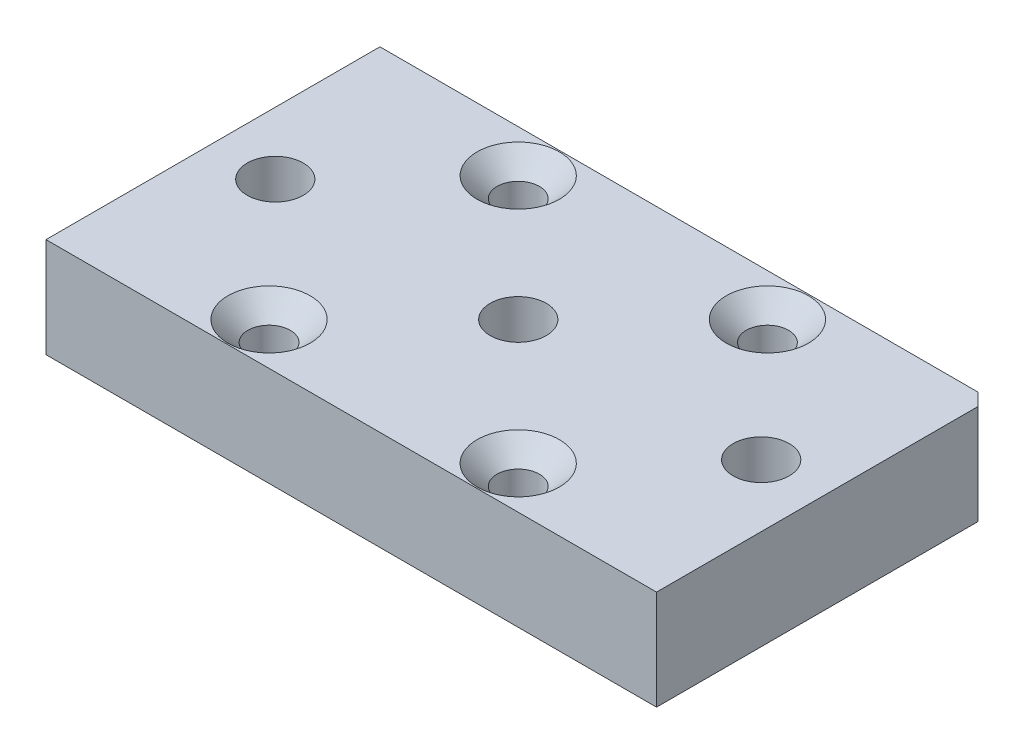
SolidWorks part; units mm, degrees
ref_plane "前视基准面" through (0, 0, 0) normal (0, 0, 1) x (1, 0, 0)
ref_plane "上视基准面" through (0, 0, 0) normal (0, 1, 0) x (1, 0, 0)
ref_plane "右视基准面" through (0, 0, 0) normal (1, 0, 0) x (0, 0, -1)
other "Configuration Table"
sketch "草图1" plane through (0, 0, 0) normal (0, 1, 0) x (1, 0, 0)
  line L1 (-24.5, -13.4) -> (24.5, -13.4)
  line L2 (-24.5, -13.4) -> (-24.5, 13.4)
  line L3 (-24.5, 13.4) -> (24.5, 13.4)
  line L4 (24.5, -13.4) -> (24.5, 13.4)
  line L5 (-24.5, -13.4) -> (24.5, 13.4) construction
  line L6 (-24.5, 13.4) -> (24.5, -13.4) construction
  point P0 (0, 0)
  dimension "D1" = 49
  dimension "D2" = 26.8
extrude "凸台-拉伸1" add sketch "草图1" along normal blind 8
hole_wizard "M3 十字槽沉头木螺钉的锥形沉头孔1" positions "草图2" profile "草图3" countersink size "M3" standard "GB" end condition through all
sketch "草图2" plane through (0, 8, 0) normal (0, 1, 0) x (1, 0, 0)
  line L0 (24.5, 13.4) -> (-24.5, 13.4) construction
  line L1 (-24.5, -13.4) -> (24.5, -13.4) construction
  line L2 (-24.5, 13.4) -> (-24.5, -13.4) construction
  line L3 (24.5, -13.4) -> (24.5, 13.4) construction
  point P0 (-10, -10)
  point P2 (10, -10)
  point P4 (10, 10)
  point P6 (-10, 10)
  dimension "D1" = 3.4
  dimension "D2" = 3.4
  dimension "D3" = 3.4
  dimension "D4" = 3.4
  dimension "D5" = 14.5
  dimension "D6" = 14.5
  dimension "D7" = 14.5
  dimension "D8" = 14.5
sketch "草图3" plane through (-10, 8, 10) normal (1, 0, 0) x (0, 0, 1)
  line L0 (0, 0) -> (0, 8)
  line L1 (0, 8) -> (1.7, 8)
  line L2 (1.7, 8) -> (1.7, 1.6)
  line L3 (1.7, 1.6) -> (3.3, 0)
  line L5 (3.3, 0) -> (0, 0)
  line L6 (-1.7, 1.6) -> (-3.3, 0) construction
  line L11 (0, -6.35) -> (0, 107.95) construction
  dimension "通孔孔直径" = 3.4
  dimension "通孔孔深度" = 8
  dimension "近端锥形沉头孔直径" = 6.6
  dimension "近端锥形沉头孔角度" = 90
hole_wizard "M4 十字槽沉头木螺钉的锥形沉头孔1" positions "草图4" profile "草图5" countersink size "M4" standard "GB" end condition through all
sketch "草图4" plane through (0, 0, 0) normal (0, -1, 0) x (-1, 0, 0)
  line L0 (-24.5, 0) -> (24.5, 0) construction
  line L1 (-24.5, -13.4) -> (-24.5, 13.4) construction
  line L2 (24.5, 13.4) -> (24.5, -13.4) construction
  point P0 (19.5, 0)
  point P2 (0, 0)
  point P4 (-19.5, 0)
  dimension "D1" = 5
  dimension "D2" = 5
sketch "草图5" plane through (-19.5, 0, 0) normal (1, 0, 0) x (0, 0, -1)
  line L0 (0, 0) -> (0, 8)
  line L1 (0, 8) -> (2.25, 8)
  line L2 (2.25, 8) -> (2.25, 2.05)
  line L3 (2.25, 2.05) -> (4.3, 0)
  line L5 (4.3, 0) -> (0, 0)
  line L6 (-2.25, 2.05) -> (-4.3, 0) construction
  line L11 (0, -6.35) -> (0, 107.95) construction
  dimension "通孔孔直径" = 4.5
  dimension "通孔孔深度" = 8
  dimension "近端锥形沉头孔直径" = 8.6
  dimension "近端锥形沉头孔角度" = 90
chamfer "倒角1" distance 1 angle 45 1 edges at (24.5, 4, -13.4)
